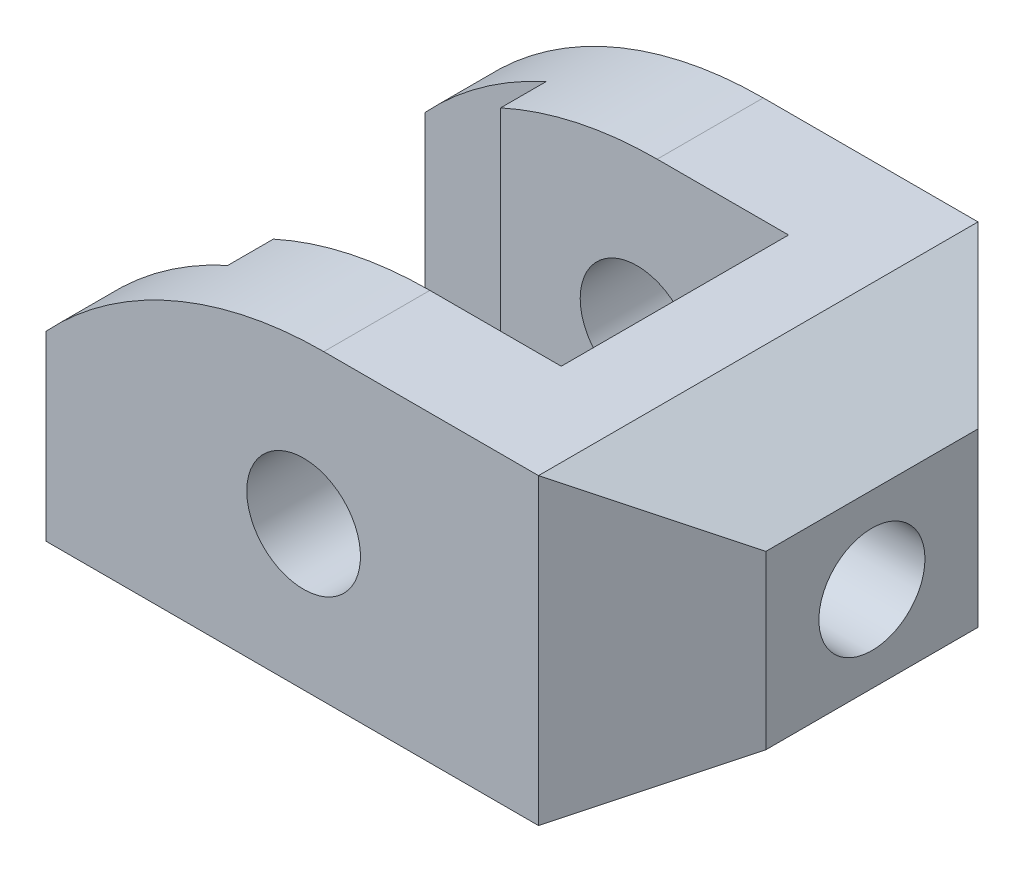
SolidWorks part; units mm, degrees
material "1060 Alloy"
ref_plane "Front Plane" through (0, 0, 0) normal (0, 0, 1) x (1, 0, 0)
ref_plane "Top Plane" through (0, 0, 0) normal (0, 1, 0) x (1, 0, 0)
ref_plane "Right Plane" through (0, 0, 0) normal (1, 0, 0) x (0, 0, -1)
sketch "Sketch1" plane through (0, 0, 0) normal (0, 0, 1) x (1, 0, 0)
  line L0 (0, 0) -> (65, 0)
  line L1 (65, 0) -> (80, 8.6603)
  line L2 (80, 8.6603) -> (80, 31.3397)
  line L3 (80, 31.3397) -> (65, 40)
  line L4 (65, 40) -> (36.6606, 40)
  line L5 (0, 0) -> (0, 24)
  arc A0 (0, 24) -> (36.6606, 40) centre (36.6606, -10) cw
  circle A1 centre (34, 19) radius 7.5
  dimension "D8" = 50
  dimension "D9" = 15
  dimension "D1" = 24
  dimension "D2" = 65
  dimension "D3" = 15
  dimension "D4" = 30
  dimension "D5" = 15
  dimension "D6" = 30
  dimension "D7" = 40
  dimension "D10" = 19
  dimension "D11" = 31
extrude "Boss-Extrude1" add sketch "Sketch1" along normal mid plane 58
sketch "Sketch2" plane through (0, 0, 0) normal (0, 1, 0) x (1, 0, 0)
  line L0 (0, -29) -> (0, 29) construction
  line L1 (0, 21) -> (16, 21)
  line L2 (0, 21) -> (0, -21)
  line L3 (0, -21) -> (16, -21)
  line L5 (36.6606, -29) -> (36.6606, 29) construction
  line L6 (16, -15) -> (54, -15)
  line L8 (16, 15) -> (54, 15)
  line L9 (54, -15) -> (54, 15)
  line L10 (0, -29) -> (36.6606, -29) construction
  line L11 (16, 21) -> (16, 15)
  line L12 (65, -29) -> (65, 29) construction
  line L13 (36.6606, 29) -> (0, 29) construction
  line L14 (16, -15) -> (16, -21)
  point P6 (36.6606, 0)
  dimension "D1" = 11
  dimension "D2" = 8
  dimension "D3" = 16
  dimension "D4" = 6
  dimension "D5" = 6
  dimension "D6" = 8
extrude "Cut-Extrude1" cut sketch "Sketch2" along normal blind 72
sketch "Sketch3" plane through (0, 0, 0) normal (0, 1, 0) x (1, 0, 0)
  line L0 (80, 29) -> (65, 29)
  line L1 (65, 29) -> (80, 14)
  line L2 (80, -29) -> (80, 29) construction
  line L3 (80, 14) -> (80, 29)
  line L4 (65, -29) -> (80, -29)
  line L5 (80, -29) -> (80, -14)
  line L6 (80, -14) -> (65, -29)
  dimension "D1" = 45
  dimension "D2" = 45
extrude "Cut-Extrude2" cut sketch "Sketch3" along normal blind 72
sketch "Sketch4" plane through (80, 0, 0) normal (1, 0, 0) x (0, 0, -1)
  line L0 (-29, 40) -> (-29, 0) construction
  line L1 (-29, 0) -> (29, 0) construction
  circle A0 centre (0, 20) radius 7
  dimension "D3" = 14
  dimension "D1" = 29
  dimension "D2" = 20
extrude "Cut-Extrude3" cut sketch "Sketch4" against normal blind 72
equation "\"A\"= 58mm"
equation "\"B\"= 40mm"
equation "\"C\"= 65mm"
equation "\"D2@Sketch1\"=\"C\""
equation "\"D7@Sketch1\"=\"B\""
equation "\"D1@Boss-Extrude1\"=\"A\""
equation "\"D2@Sketch4\"=\"B\"/2"
equation "\"D1@Sketch4\"=\"A\"/2"
